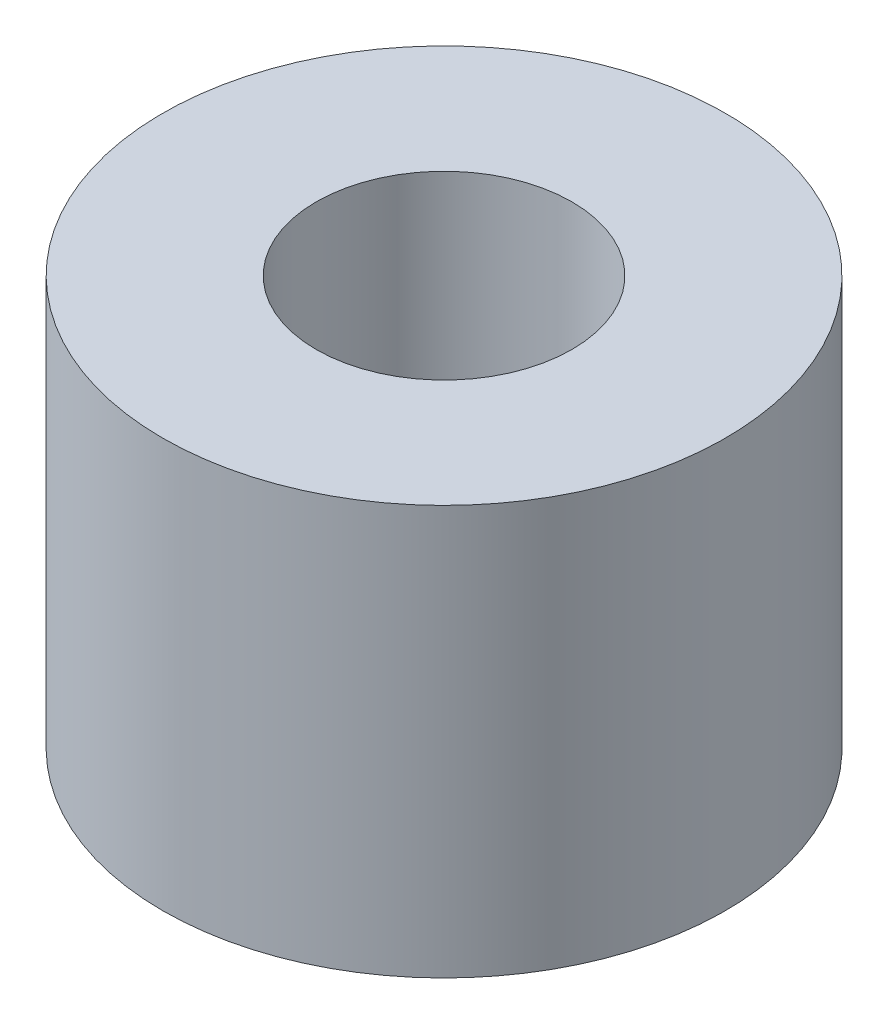
SolidWorks part; units mm, degrees
ref_plane "前视基准面" through (0, 0, 0) normal (0, 0, 1) x (1, 0, 0)
ref_plane "上视基准面" through (0, 0, 0) normal (0, 1, 0) x (1, 0, 0)
ref_plane "右视基准面" through (0, 0, 0) normal (1, 0, 0) x (0, 0, -1)
sketch "草图1" plane through (0, 0, 0) normal (0, 1, 0) x (1, 0, 0)
  circle A0 centre (0, 0) radius 2.5
  circle A1 centre (0, 0) radius 5.5
  dimension "D1" = 5
  dimension "D2" = 11
extrude "凸台-拉伸1" add sketch "草图1" along normal blind 8
